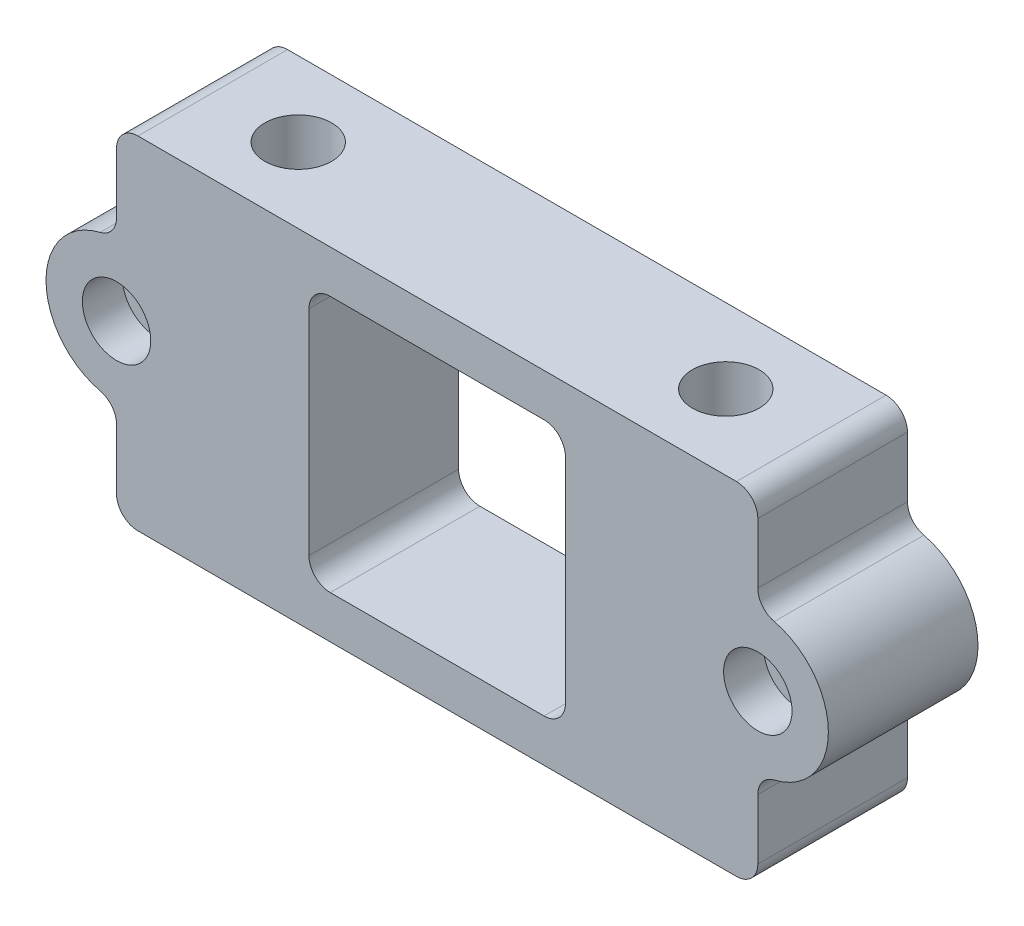
SolidWorks part; units mm, degrees
material "6061-T6 (SS)"
ref_plane "X-Y Datum" through (0, 0, 0) normal (0, 0, 1) x (1, 0, 0)
ref_plane "X-Z Datum" through (0, 0, 0) normal (0, 1, 0) x (1, 0, 0)
ref_plane "Y-Z Datum" through (0, 0, 0) normal (1, 0, 0) x (0, 0, -1)
other "Graphic1"
other "Graphic (Closed) -1"
other "Graphic2"
other "Graphic (Closed) -2"
other "Graphic3"
other "Graphic (Closed) -3"
sketch "Sketch1" plane through (0, 0, 0) normal (0, 0, 1) x (1, 0, 0)
  line L5 (-93.6625, 0) -> (0, 0) construction
  line L7 (-93.6625, -20.32) -> (-93.6625, 20.32)
  line L17 (-93.6625, -20.32) -> (0, -20.32)
  line L30 (-93.6625, 20.32) -> (0, 20.32)
  line L31 (0, 20.32) -> (0, -20.32)
  circle A4 centre (-84.9313, 0) radius 2.4892
  circle A7 centre (-8.7312, 0) radius 2.4892
  point P1 (-93.6625, 0)
  dimension "D2" = 93.6625
  dimension "D3" = 8.7312
  dimension "D1" = 8.7312
  dimension "D4" = 40.64
extrude "Boss-Extrude1" add sketch "Sketch1" against normal blind 17.78
sketch "Sketch3" plane through (0, 0, 0) normal (0, 0, 1) x (1, 0, 0)
  circle A2 centre (-84.9313, 0) radius 4.064
  circle A3 centre (-84.9313, 0) radius 2.4892 construction
  circle A4 centre (-8.7312, 0) radius 4.064
  dimension "D1" = 8.128
sketch "Sketch6" plane through (0, 20.32, 0) normal (0, 1, 0) x (1, 0, 0)
  line L0 (0, 17.78) -> (-93.6625, 17.78) construction
  line L1 (-72.2313, 8.89) -> (-21.4312, 8.89) construction
  circle A0 centre (-72.2313, 8.89) radius 3.9687
  circle A1 centre (-21.4312, 8.89) radius 3.9687
  point P4 (-46.8312, 17.78)
  point P5 (-46.8312, 8.89)
  dimension "D1" = 7.9375
  dimension "D2" = 8.89
  dimension "D3" = 50.8
extrude "Cut-Extrude4" cut sketch "Sketch6" against normal through all
sketch "Sketch5" plane through (0, 0, 0) normal (0, 0, 1) x (1, 0, 0)
  line L7 (-46.8312, 20.32) -> (-46.8313, -20.32) construction
  line L8 (0, 20.32) -> (-93.6625, 20.32) construction
  line L18 (-93.6625, -20.32) -> (0, -20.32) construction
  line B0 (-93.6625, -20.32) -> (-93.6625, 20.32)
  line B1 (-84.9312, -20.32) -> (-93.6625, -20.32)
  line B2 (-84.9313, -10.6225) -> (-84.9312, -20.32)
  line B3 (-84.9313, 10.6225) -> (-84.9312, 20.32)
  line B4 (-93.6625, 20.32) -> (-84.9312, 20.32)
  arc B5 (-84.9313, -10.6225) -> (-86.8806, -8.1522) centre (-87.4713, -10.6225) ccw
  arc B6 (-86.8806, 8.1522) -> (-86.8806, -8.1522) centre (-84.9313, 0) ccw
  arc B7 (-84.9313, 10.6225) -> (-86.8806, 8.1522) centre (-87.4713, 10.6225) cw
  line B8 (0, -20.32) -> (0, 20.32)
  line B9 (-8.7313, -20.32) -> (0, -20.32)
  line B10 (-8.7313, -10.6225) -> (-8.7313, -20.32)
  line B11 (-8.7312, 10.6225) -> (-8.7312, 20.32)
  line B12 (0, 20.32) -> (-8.7312, 20.32)
  arc B13 (-8.7313, -10.6225) -> (-6.7819, -8.1522) centre (-6.1912, -10.6225) cw
  arc B14 (-6.7819, 8.1522) -> (-6.7819, -8.1522) centre (-8.7312, 0) cw
  arc B15 (-8.7312, 10.6225) -> (-6.7819, 8.1522) centre (-6.1912, 10.6225) ccw
sketch_block_instance "Block1-1"
sketch_block "Block1"
sketch_block_instance "Block1-2"
extrude "Cut-Extrude3" cut sketch "Sketch5" against normal up to surface (17.78 mm away) up to face at (-6.242, 0, -17.78)
fillet "Fillet1" radius 2.54 4 edges at (-84.9312, -20.32, -8.89) (-8.7313, -20.32, -8.89) (-8.7312, 20.32, -8.89) (-84.9312, 20.32, -8.89)
extrude "Cut-Extrude5" cut sketch "Sketch3" against normal blind 4.7752
ref_point "Point1"
ref_point "Point2"
sketch "Sketch7" plane through (0, 0, 0) normal (0, 0, 1) x (1, 0, 0)
  line L0 (-46.8312, 20.32) -> (-46.8313, -20.32) construction
  line L5 (-11.2713, 20.32) -> (-82.3912, 20.32) construction
  line L6 (-82.3912, -20.32) -> (-11.2713, -20.32) construction
  line L8 (-59.5313, -15.24) -> (-34.1313, -15.24)
  line L9 (-62.0713, -12.7) -> (-62.0713, 12.7)
  line L10 (-59.5313, 15.24) -> (-34.1313, 15.24)
  line L11 (-31.5913, -12.7) -> (-31.5913, 12.7)
  line L12 (-62.0712, -15.24) -> (-31.5913, 15.24) construction
  line L13 (-62.0712, 15.24) -> (-31.5913, -15.24) construction
  arc A0 (-59.5313, -15.24) -> (-62.0713, -12.7) centre (-59.5313, -12.7) cw
  arc A1 (-34.1313, -15.24) -> (-31.5913, -12.7) centre (-34.1313, -12.7) ccw
  arc A2 (-34.1313, 15.24) -> (-31.5913, 12.7) centre (-34.1313, 12.7) cw
  arc A3 (-62.0713, 12.7) -> (-59.5313, 15.24) centre (-59.5313, 12.7) cw
  point P0 (-46.8313, 0)
  dimension "D3" = 2.54
  dimension "D1" = 30.48
  dimension "D2" = 30.48
extrude "Cut-Extrude6" cut sketch "Sketch7" against normal through all
